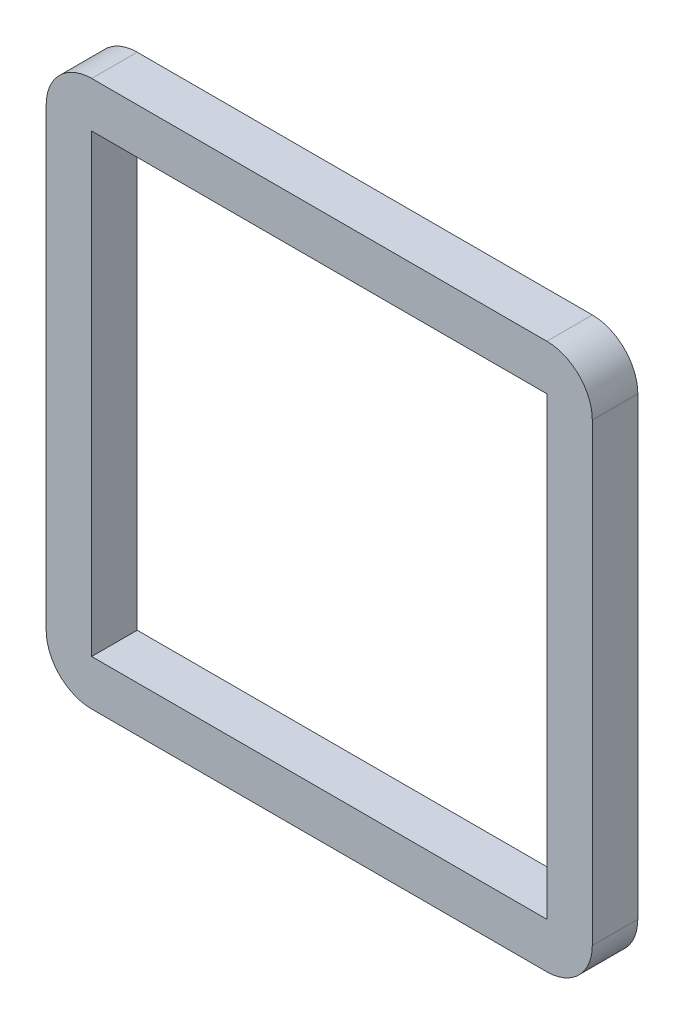
SolidWorks part; units mm, degrees
ref_plane "Front Plane" through (0, 0, 0) normal (0, 0, 1) x (1, 0, 0)
ref_plane "Top Plane" through (0, 0, 0) normal (0, 1, 0) x (1, 0, 0)
ref_plane "Right Plane" through (0, 0, 0) normal (1, 0, 0) x (0, 0, -1)
sketch "Sketch1" plane through (0, 0, 0) normal (0, 0, 1) x (1, 0, 0)
  line L1 (-50, 60) -> (50, 60)
  line L2 (-60, 50) -> (-60, -50)
  line L3 (-50, -60) -> (50, -60)
  line L4 (60, 50) -> (60, -50)
  line L5 (-60, 60) -> (60, -60) construction
  line L6 (-60, -60) -> (60, 60) construction
  arc A0 (-60, -50) -> (-50, -60) centre (-50, -50) ccw
  arc A1 (50, -60) -> (60, -50) centre (50, -50) ccw
  arc A2 (50, 60) -> (60, 50) centre (50, 50) cw
  arc A3 (-50, 60) -> (-60, 50) centre (-50, 50) ccw
  point P0 (0, 0)
  dimension "D3" = 10
  dimension "D1" = 120
  dimension "D2" = 120
extrude "Boss-Extrude1" add sketch "Sketch1" along normal blind 10 contours A3 L2 A0 L3 A1 L4 A2 L1
sketch "Sketch2" plane through (0, 0, 10) normal (0, 0, 1) x (1, 0, 0)
  line L0 (0, 0) -> (0, 40) construction
  line L1 (-50, 50) -> (50, 50) construction
  line L2 (-50, 50) -> (-50, -50) construction
  line L3 (-50, -50) -> (50, -50) construction
  line L4 (50, 50) -> (50, -50) construction
  line L5 (-50, 50) -> (50, -50) construction
  line L6 (-50, -50) -> (50, 50) construction
  line L7 (0, 40) -> (-40, 40) construction
  line L8 (-40, 40) -> (-40, 0) construction
  line L9 (-40, 0) -> (0, 0) construction
  line L11 (0, 20) -> (-20, 20) construction
  line L12 (-20, 40) -> (-20, 20) construction
  circle A0 centre (0, 40) radius 4 construction
  circle A1 centre (0, 20) radius 4 construction
  circle A2 centre (0, 0) radius 4 construction
  circle A3 centre (-20, 20) radius 4 construction
  circle A4 centre (-20, 40) radius 4 construction
  circle A5 centre (-40, 40) radius 4 construction
  circle A6 centre (0, 0) radius 4 construction
  circle A7 centre (20, 0) radius 4 construction
  circle A8 centre (40, 0) radius 4 construction
  circle A9 centre (40, 20) radius 4 construction
  circle A10 centre (40, 40) radius 4 construction
  circle A11 centre (20, 20) radius 4 construction
  circle A12 centre (0, 0) radius 4 construction
  circle A13 centre (0, -20) radius 4 construction
  circle A14 centre (0, -40) radius 4 construction
  circle A15 centre (20, -40) radius 4 construction
  circle A16 centre (40, -40) radius 4 construction
  circle A17 centre (20, -20) radius 4 construction
  circle A18 centre (0, 0) radius 4
  circle A19 centre (-20, 0) radius 4 construction
  circle A20 centre (-40, 0) radius 4 construction
  circle A21 centre (-40, -20) radius 4 construction
  circle A22 centre (-40, -40) radius 4 construction
  circle A23 centre (-20, -20) radius 4 construction
  point P0 (0, 0)
  point P55 (0, 0)
  dimension "D4" = 8
  dimension "D1" = 100
  dimension "D2" = 100
  dimension "D3" = 40
  dimension "D5" = 4
sketch "Sketch3" plane through (0, 0, 10) normal (0, 0, 1) x (1, 0, 0)
  line L1 (-50, 50) -> (50, 50)
  line L2 (-50, 50) -> (-50, -50)
  line L3 (-50, -50) -> (50, -50)
  line L4 (50, 50) -> (50, -50)
  line L5 (-50, 50) -> (50, -50) construction
  line L6 (-50, -50) -> (50, 50) construction
  point P0 (0, 0)
extrude "Cut-Extrude1" cut sketch "Sketch3" against normal blind 10
